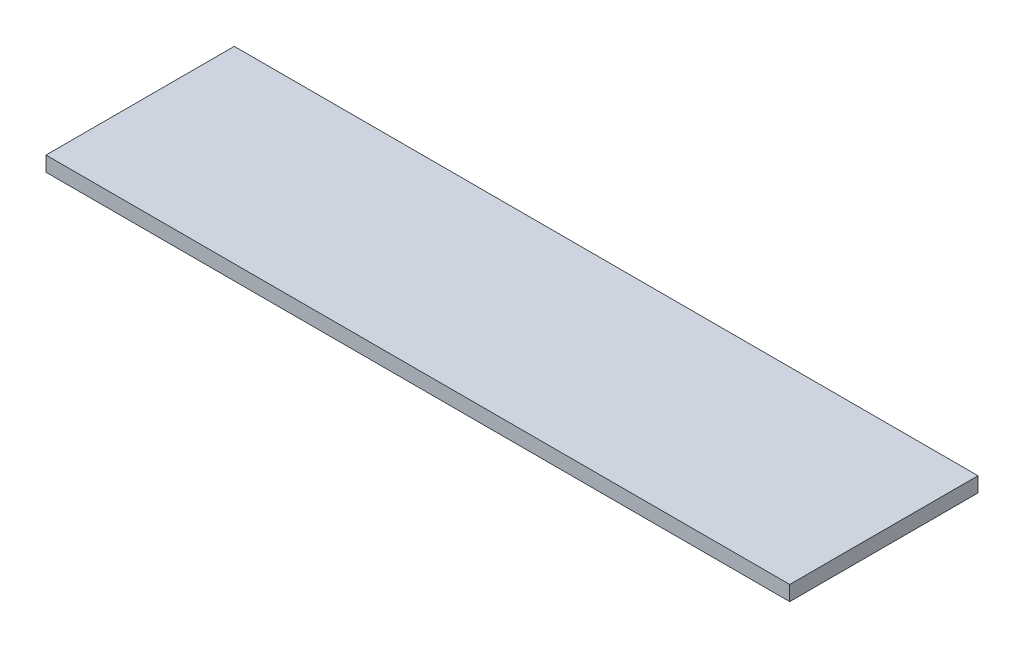
SolidWorks part; units mm, degrees
material "Кедр"
ref_plane "Спереди" through (0, 0, 0) normal (0, 0, 1) x (1, 0, 0)
ref_plane "Сверху" through (0, 0, 0) normal (0, 1, 0) x (1, 0, 0)
ref_plane "Справа" through (0, 0, 0) normal (1, 0, 0) x (0, 0, -1)
sketch "Эскиз1" plane through (0, 0, 0) normal (0, 1, 0) x (1, 0, 0)
  line L1 (-149.51, -37.8507) -> (149.51, -37.8507)
  line L2 (-149.51, -37.8507) -> (-149.51, 37.8507)
  line L3 (-149.51, 37.8507) -> (-82.8034, 37.8507)
  line L4 (149.51, -37.8507) -> (149.51, 37.8507)
  line L5 (-149.51, -37.8507) -> (149.51, 37.8507) construction
  line L6 (-149.51, 37.8507) -> (149.51, -37.8507) construction
  line L7 (-82.8034, 106.8823) -> (-82.8034, 71.8823) construction
  line L10 (7.6879, 37.8507) -> (149.51, 37.8507)
  line L11 (-82.8034, 37.8507) -> (7.6879, 37.8507)
  point P0 (0, 0)
extrude "Бобышка-Вытянуть1" add sketch "Эскиз1" along normal blind 6
sketch "Эскиз2" plane through (0, 6, 0) normal (0, 1, 0) x (1, 0, 0)
  line L1 (0, -37.8507) -> (0, 37.8507) construction
  line L2 (-149.51, -37.8507) -> (149.51, -37.8507) construction
  line L3 (149.51, 37.8507) -> (-149.51, 37.8507) construction
